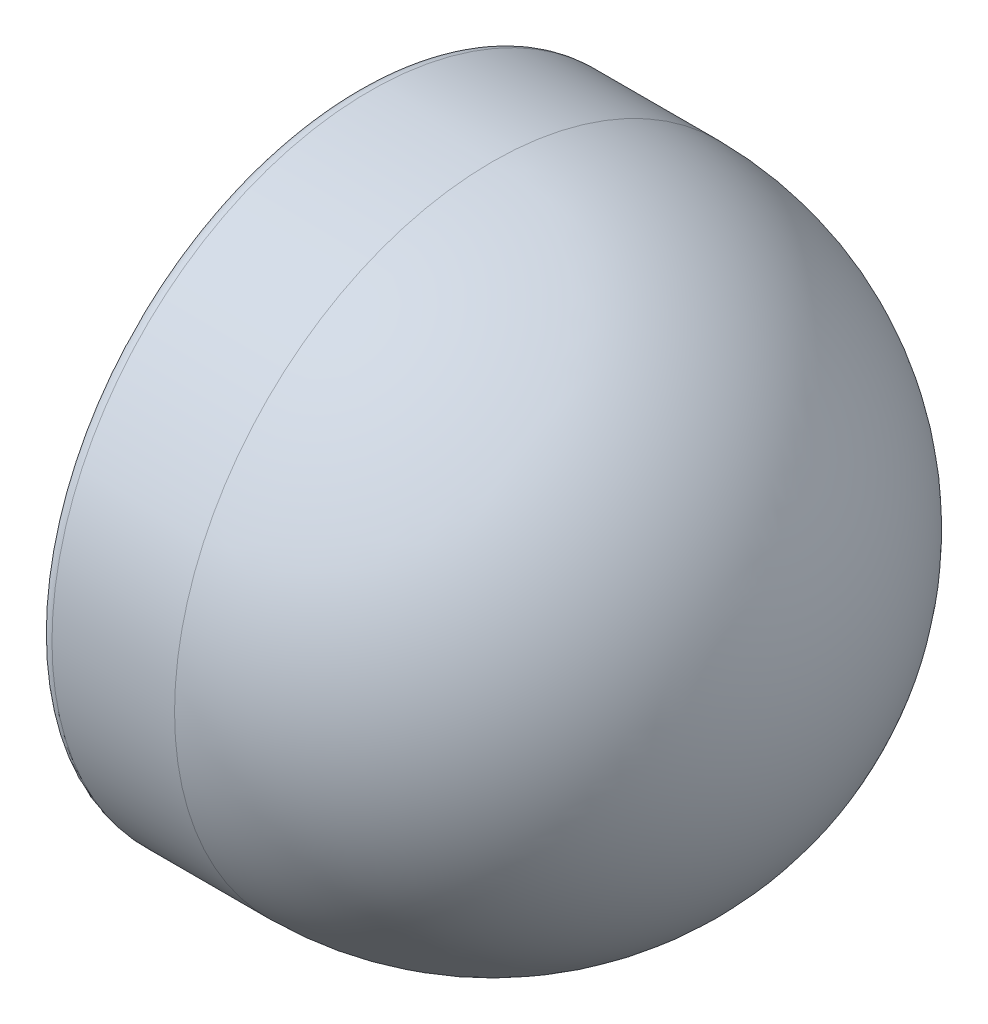
SolidWorks part; units mm, degrees
ref_plane "Front Plane" through (0, 0, 0) normal (0, 0, 1) x (1, 0, 0)
ref_plane "Top Plane" through (0, 0, 0) normal (0, 1, 0) x (1, 0, 0)
ref_plane "Right Plane" through (0, 0, 0) normal (1, 0, 0) x (0, 0, -1)
sketch "Sketch1" plane through (0, 0, 0) normal (0, 0, 1) x (1, 0, 0)
  line L0 (-70, 0) -> (71.8421, 0) construction
  line L1 (-70, 70) -> (-97, 70)
  line L2 (-100, 67) -> (-100, 61.5)
  line L3 (-98.5, 60) -> (-96.6213, 60)
  line L4 (-95.5607, 60.4393) -> (-92.4838, 63.5162)
  line L5 (-70, 69) -> (-97, 69)
  line L6 (-99, 67) -> (-99, 61.5)
  line L7 (-98.5, 61) -> (-96.6213, 61)
  line L8 (-96.2678, 61.1464) -> (-93.1909, 64.2233)
  line L9 (-93.1909, 64.2233) -> (-92.4838, 63.5162)
  line L10 (-1, 0) -> (0, 0)
  arc A0 (0, 0) -> (-70, 70) centre (-70, 0) ccw
  arc A1 (-97, 70) -> (-100, 67) centre (-97, 67) ccw
  arc A2 (-96.6213, 60) -> (-95.5607, 60.4393) centre (-96.6213, 61.5) ccw
  arc A3 (-100, 61.5) -> (-98.5, 60) centre (-98.5, 61.5) ccw
  arc A4 (-1, 0) -> (-70, 69) centre (-70, 0) ccw
  arc A5 (-97, 69) -> (-99, 67) centre (-97, 67) ccw
  arc A6 (-99, 61.5) -> (-98.5, 61) centre (-98.5, 61.5) ccw
  arc A7 (-96.6213, 61) -> (-96.2678, 61.1464) centre (-96.6213, 61.5) ccw
  point P12 (-100, 70)
  point P15 (-96, 60)
  point P18 (-100, 60)
  dimension "D1" = 70
  dimension "D6" = 3
  dimension "D7" = 1.5
  dimension "D2" = 30
  dimension "D3" = 10
  dimension "D4" = 4
  dimension "D5" = 135
  dimension "D8" = 1
revolve "Revolve1" add sketch "Sketch1" angle 360 about L0
